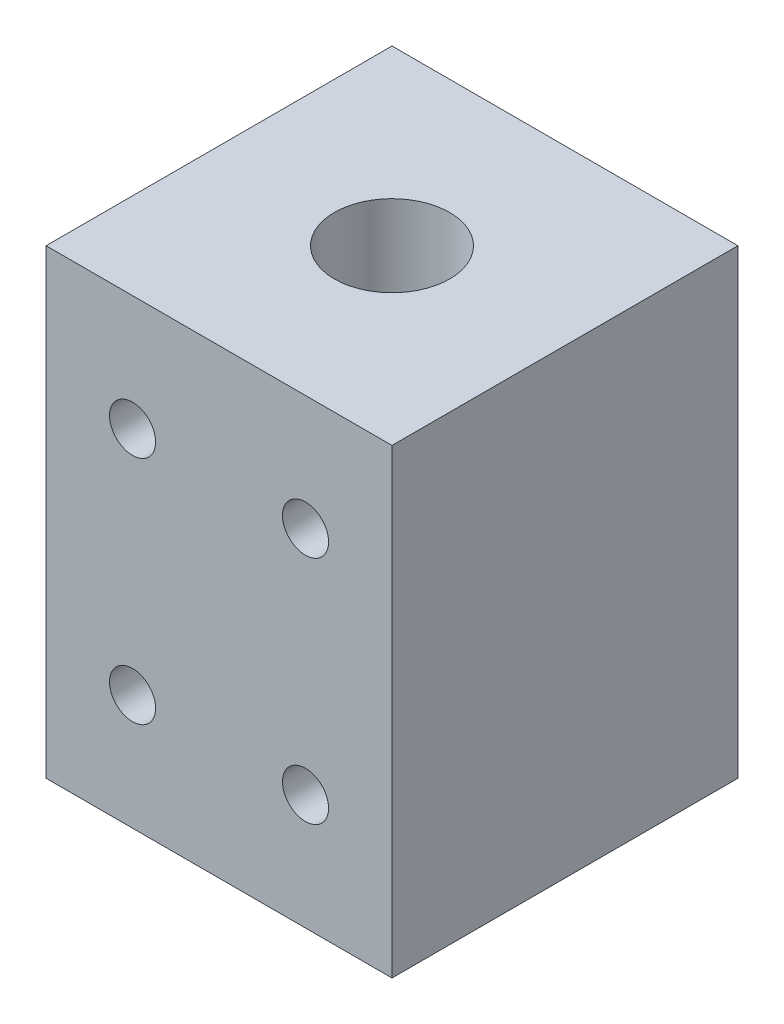
SolidWorks part; units mm, degrees
material "Aleación 1060"
ref_plane "Alzado" through (0, 0, 0) normal (0, 0, 1) x (1, 0, 0)
ref_plane "Planta" through (0, 0, 0) normal (0, 1, 0) x (1, 0, 0)
ref_plane "Vista lateral" through (0, 0, 0) normal (1, 0, 0) x (0, 0, -1)
sketch "Croquis1" plane through (0, 0, 0) normal (0, 1, 0) x (1, 0, 0)
  line L1 (30, -30) -> (-30, -30)
  line L2 (30, -30) -> (30, 30)
  line L3 (30, 30) -> (-30, 30)
  line L4 (-30, -30) -> (-30, 30)
  line L5 (30, -30) -> (-30, 30) construction
  line L6 (30, 30) -> (-30, -30) construction
  circle A0 centre (0, 0) radius 10
  point P0 (0, 0)
  dimension "D2" = 20
  dimension "D1" = 60
extrude "Saliente-Extruir1" add sketch "Croquis1" along normal blind 80
sketch "Croquis2" plane through (0, 0, 30) normal (0, 0, 1) x (1, 0, 0)
  line L1 (15, 20) -> (-15, 20) construction
  line L2 (15, 20) -> (15, 60) construction
  line L3 (15, 60) -> (-15, 60) construction
  line L4 (-15, 20) -> (-15, 60) construction
  line L5 (15, 20) -> (-15, 60) construction
  line L6 (15, 60) -> (-15, 20) construction
  circle A0 centre (-15, 60) radius 4
  circle A1 centre (15, 60) radius 4
  circle A2 centre (-15, 20) radius 4
  circle A3 centre (15, 20) radius 4
  point P0 (0, 40)
  dimension "D1" = 40
  dimension "D2" = 30
extrude "Cortar-Extruir1" cut sketch "Croquis2" against normal blind 20
